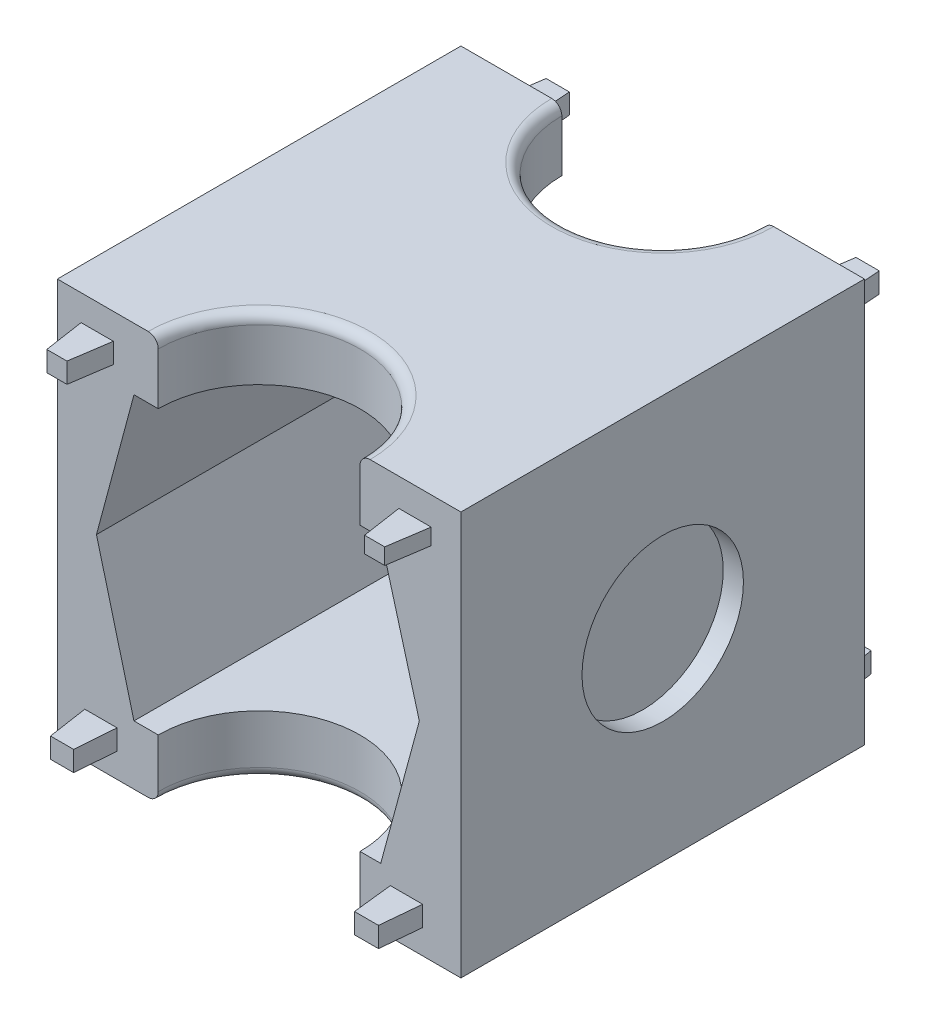
SolidWorks part; units mm, degrees
ref_plane "Front Plane" through (0, 0, 0) normal (0, 0, 1) x (1, 0, 0)
ref_plane "Top Plane" through (0, 0, 0) normal (0, 1, 0) x (1, 0, 0)
ref_plane "Right Plane" through (0, 0, 0) normal (1, 0, 0) x (0, 0, -1)
sketch "Sketch1" plane through (0, 0, 0) normal (1, 0, 0) x (0, 0, -1)
  line L0 (-50, 50) -> (50, 50)
  line L3 (-50, 50) -> (-50, -50)
  line L4 (-50, -50) -> (50, -50)
  line L5 (50, -50) -> (50, 50)
extrude "Boss-Extrude1" add sketch "Sketch1" along normal blind 100
sketch "Sketch2" plane through (0, 0, 0) normal (-1, 0, 0) x (0, 0, 1)
  circle A0 centre (0, 0) radius 20
extrude "Cut-Extrude1" cut sketch "Sketch2" against normal blind 5
sketch "Sketch3" plane through (100, 0, 0) normal (1, 0, 0) x (0, 0, -1)
  circle A0 centre (0, 0) radius 20
extrude "Cut-Extrude2" cut sketch "Sketch3" against normal blind 5
sketch "Sketch4" plane through (0, 0, -50) normal (0, 0, -1) x (-1, 0, 0)
  line L6 (-80.1289, 34.6594) -> (-18.9866, 34.6594)
  line L15 (-80.1289, -35.3406) -> (-18.9866, -35.3406)
  line L17 (-80.1289, 34.6594) -> (-89.6912, 0)
  line L18 (-89.6912, 0) -> (-80.1289, -35.3406)
  line L19 (-18.9866, 34.6594) -> (-9.6912, 0)
  line L20 (-9.6912, 0) -> (-18.9866, -35.3406)
extrude "Cut-Extrude3" cut sketch "Sketch4" against normal through all
sketch "Sketch15" plane through (0, 50, 0) normal (0, 1, 0) x (1, 0, 0)
  line L0 (100, -50) -> (0, -50) construction
  arc A0 (75, -50) -> (25, -50) centre (50, -50) ccw
extrude "Cut-Extrude5" cut sketch "Sketch15" against normal through all and the other way through all
sketch "Sketch16" plane through (0, 50, 0) normal (0, 1, 0) x (1, 0, 0)
  line L0 (100, 50) -> (0, 50) construction
  arc A0 (25, 50) -> (75, 50) centre (50, 50) ccw
extrude "Cut-Extrude6" cut sketch "Sketch16" against normal through all and the other way through all
fillet "Fillet3" radius 2.5 4 edges at (50, -50, -25) (50, -50, 25) (50, 50, -25) (50, 50, 25)
sketch "Sketch17" plane through (0, 0, 50) normal (0, 0, 1) x (1, 0, 0)
  line L2 (84.6212, 43.0797) -> (92.6212, 43.0797)
  line L3 (84.6212, 39.0797) -> (92.6212, 39.0797)
  arc A0 (84.6212, 43.0797) -> (84.6212, 39.0797) centre (84.6212, 41.0797) ccw
  arc A1 (92.6212, 39.0797) -> (92.6212, 43.0797) centre (92.6212, 41.0797) ccw
extrude "Boss-Extrude3" add sketch "Sketch17" along normal blind 10
sketch "Sketch18" plane through (0, 43.0797, 0) normal (0, 1, 0) x (1, 0, 0)
  line L1 (92.6212, -60) -> (84.6212, -60) construction
  line L4 (84.6212, -50) -> (86.1212, -60)
  line L5 (84.6212, -50) -> (82.6212, -50)
  line L6 (82.6212, -50) -> (82.6212, -60)
  line L7 (82.6212, -60) -> (86.1212, -60)
extrude "Cut-Extrude8" cut sketch "Sketch18" against normal blind 10
sketch "Sketch20" plane through (0, 43.0797, 0) normal (0, 1, 0) x (1, 0, 0)
  line L0 (91.1212, -60) -> (94.6212, -60)
  line L1 (92.6212, -60) -> (86.1212, -60) construction
  line L2 (91.1212, -60) -> (92.6212, -50)
  line L3 (94.6212, -60) -> (94.6212, -50)
  line L4 (94.6212, -50) -> (92.6212, -50)
extrude "Cut-Extrude9" cut sketch "Sketch20" against normal blind 10
sketch "Sketch24" plane through (0, 0, 50) normal (0, 0, 1) x (1, 0, 0)
  line L2 (5.8822, 43.5797) -> (13.8822, 43.5797)
  line L3 (5.8822, 38.5797) -> (13.8822, 38.5797)
  arc A0 (5.8822, 43.5797) -> (5.8822, 38.5797) centre (5.8822, 41.0797) ccw
  arc A1 (13.8822, 38.5797) -> (13.8822, 43.5797) centre (13.8822, 41.0797) ccw
extrude "Boss-Extrude4" add sketch "Sketch24" along normal blind 10
sketch "Sketch25" plane through (0, 43.5797, 0) normal (0, 1, 0) x (1, 0, 0)
  line L0 (3.3822, -50) -> (5.8822, -50)
  line L1 (13.8822, -60) -> (5.8822, -60) construction
  line L3 (3.3822, -50) -> (3.3822, -60)
  line L4 (3.3822, -60) -> (7.3822, -60)
  line L5 (5.8822, -50) -> (7.3822, -60)
extrude "Cut-Extrude11" cut sketch "Sketch25" against normal blind 10
sketch "Sketch26" plane through (0, 43.5797, 0) normal (0, 1, 0) x (1, 0, 0)
  line L1 (13.8822, -60) -> (7.3822, -60) construction
  line L2 (12.3822, -60) -> (13.8822, -50)
  line L3 (13.8822, -50) -> (16.3822, -50)
  line L4 (16.3822, -50) -> (16.3822, -60)
  line L5 (16.3822, -60) -> (12.3822, -60)
extrude "Cut-Extrude12" cut sketch "Sketch26" against normal blind 10
sketch "Sketch27" plane through (0, 0, 50) normal (0, 0, 1) x (1, 0, 0)
  line L2 (6.7979, -43.9203) -> (14.7979, -43.9203)
  line L3 (6.7979, -38.9203) -> (14.7979, -38.9203)
  arc A0 (6.7979, -38.9203) -> (6.7979, -43.9203) centre (6.7979, -41.4203) ccw
  arc A1 (14.7979, -43.9203) -> (14.7979, -38.9203) centre (14.7979, -41.4203) ccw
extrude "Boss-Extrude5" add sketch "Sketch27" along normal blind 10
sketch "Sketch29" plane through (0, -43.9203, 0) normal (0, -1, 0) x (1, 0, 0)
  line L1 (6.7979, 60) -> (14.7979, 60) construction
  line L2 (8.2979, 60) -> (6.7979, 50)
  line L3 (6.7979, 50) -> (4.2979, 50)
  line L4 (4.2979, 50) -> (4.2979, 60)
  line L5 (4.2979, 60) -> (8.2979, 60)
extrude "Cut-Extrude13" cut sketch "Sketch29" against normal blind 10
sketch "Sketch30" plane through (0, -43.9203, 0) normal (0, -1, 0) x (1, 0, 0)
  line L0 (14.0479, 60) -> (17.2979, 60)
  line L4 (17.2979, 60) -> (17.2979, 50)
  line L5 (17.2979, 50) -> (14.7979, 50)
  line L6 (8.2979, 60) -> (14.7979, 60) construction
  line L7 (14.0479, 60) -> (14.7979, 50)
extrude "Cut-Extrude15" cut sketch "Sketch30" against normal blind 10
sketch "Sketch31" plane through (0, 0, 50) normal (0, 0, 1) x (1, 0, 0)
  line L2 (82.5173, -38.9203) -> (90.5173, -38.9203)
  line L3 (82.5173, -43.9203) -> (90.5173, -43.9203)
  arc A0 (82.5173, -38.9203) -> (82.5173, -43.9203) centre (82.5173, -41.4203) ccw
  arc A1 (90.5173, -43.9203) -> (90.5173, -38.9203) centre (90.5173, -41.4203) ccw
extrude "Boss-Extrude6" add sketch "Sketch31" along normal blind 10
sketch "Sketch33" plane through (0, -43.9203, 0) normal (0, -1, 0) x (1, 0, 0)
  line L1 (82.5173, 60) -> (90.5173, 60) construction
  line L2 (83.6212, 60) -> (82.5173, 50)
  line L3 (82.5173, 50) -> (80.0173, 50)
  line L4 (80.0173, 50) -> (80.0173, 60)
  line L5 (80.0173, 60) -> (83.6212, 60)
extrude "Cut-Extrude16" cut sketch "Sketch33" against normal blind 10
sketch "Sketch34" plane through (0, -43.9203, 0) normal (0, -1, 0) x (1, 0, 0)
  line L1 (83.6212, 60) -> (90.5173, 60) construction
  line L2 (89.5693, 60) -> (90.5173, 50)
  line L3 (90.5173, 50) -> (93.0173, 50)
  line L4 (93.0173, 50) -> (93.0173, 60)
  line L5 (93.0173, 60) -> (90.5173, 60) construction
  line L6 (93.0173, 50) -> (93.0173, 60) construction
  line L7 (93.0173, 60) -> (89.5693, 60)
extrude "Cut-Extrude17" cut sketch "Sketch34" against normal blind 10
sketch "Sketch35" plane through (0, 0, -50) normal (0, 0, -1) x (-1, 0, 0)
  line L2 (-17.6085, 43.5797) -> (-9.6085, 43.5797)
  line L3 (-17.6085, 38.5797) -> (-9.6085, 38.5797)
  arc A0 (-17.6085, 43.5797) -> (-17.6085, 38.5797) centre (-17.6085, 41.0797) ccw
  arc A1 (-9.6085, 38.5797) -> (-9.6085, 43.5797) centre (-9.6085, 41.0797) ccw
extrude "Boss-Extrude7" add sketch "Sketch35" along normal blind 10
sketch "Sketch36" plane through (0, 43.5797, 0) normal (0, 1, 0) x (1, 0, 0)
  line L1 (9.6085, 60) -> (17.6085, 60) construction
  line L2 (11.1085, 60) -> (9.6085, 50)
  line L3 (9.6085, 50) -> (7.1085, 50)
  line L4 (7.1085, 50) -> (7.1085, 60)
  line L5 (7.1085, 60) -> (11.1085, 60)
extrude "Cut-Extrude18" cut sketch "Sketch36" against normal blind 10
sketch "Sketch37" plane through (0, 43.5797, 0) normal (0, 1, 0) x (1, 0, 0)
  line L1 (11.1085, 60) -> (17.6085, 60) construction
  line L2 (16.8585, 60) -> (17.6085, 50)
  line L3 (17.6085, 50) -> (20.1085, 50)
  line L4 (20.1085, 50) -> (20.1085, 60)
  line L5 (20.1085, 60) -> (16.8585, 60)
extrude "Cut-Extrude19" cut sketch "Sketch37" against normal blind 10
sketch "Sketch38" plane through (0, 0, -50) normal (0, 0, -1) x (-1, 0, 0)
  line L2 (-17.3305, -38.9203) -> (-9.3305, -38.9203)
  line L3 (-17.3305, -43.9203) -> (-9.3305, -43.9203)
  arc A0 (-17.3305, -38.9203) -> (-17.3305, -43.9203) centre (-17.3305, -41.4203) ccw
  arc A1 (-9.3305, -43.9203) -> (-9.3305, -38.9203) centre (-9.3305, -41.4203) ccw
extrude "Boss-Extrude8" add sketch "Sketch38" along normal blind 10
sketch "Sketch40" plane through (0, -43.9203, 0) normal (0, -1, 0) x (1, 0, 0)
  line L1 (17.3305, -60) -> (9.3305, -60) construction
  line L2 (10.8305, -60) -> (9.3305, -50)
  line L3 (9.3305, -50) -> (6.8305, -50)
  line L4 (6.8305, -50) -> (6.8305, -60)
  line L5 (6.8305, -60) -> (10.8305, -60)
extrude "Cut-Extrude20" cut sketch "Sketch40" against normal blind 10
sketch "Sketch41" plane through (0, -43.9203, 0) normal (0, -1, 0) x (1, 0, 0)
  line L2 (16.5805, -60) -> (17.3305, -50)
  line L3 (17.3305, -50) -> (19.8305, -50)
  line L4 (19.8305, -50) -> (19.8305, -60)
  line L5 (19.8305, -60) -> (16.5805, -60)
extrude "Cut-Extrude21" cut sketch "Sketch41" against normal blind 10
sketch "Sketch42" plane through (0, 0, -50) normal (0, 0, -1) x (-1, 0, 0)
  line L2 (-94.397, 43.5797) -> (-86.397, 43.5797)
  line L3 (-94.397, 38.5797) -> (-86.397, 38.5797)
  arc A0 (-94.397, 43.5797) -> (-94.397, 38.5797) centre (-94.397, 41.0797) ccw
  arc A1 (-86.397, 38.5797) -> (-86.397, 43.5797) centre (-86.397, 41.0797) ccw
extrude "Boss-Extrude9" add sketch "Sketch42" along normal blind 10
sketch "Sketch43" plane through (0, 43.5797, 0) normal (0, 1, 0) x (1, 0, 0)
  line L1 (86.397, 60) -> (94.397, 60) construction
  line L2 (87.897, 60) -> (86.397, 50)
  line L3 (86.397, 50) -> (83.897, 50)
  line L4 (83.897, 50) -> (83.897, 60)
  line L5 (83.897, 60) -> (87.897, 60)
extrude "Cut-Extrude22" cut sketch "Sketch43" against normal blind 10
sketch "Sketch44" plane through (0, 43.5797, 0) normal (0, 1, 0) x (1, 0, 0)
  line L1 (87.897, 60) -> (94.397, 60) construction
  line L2 (93.647, 60) -> (94.397, 50)
  line L3 (94.397, 50) -> (96.897, 50)
  line L4 (96.897, 50) -> (96.897, 60)
  line L5 (96.897, 60) -> (93.647, 60)
extrude "Cut-Extrude23" cut sketch "Sketch44" against normal blind 10
sketch "Sketch45" plane through (0, 0, -50) normal (0, 0, -1) x (-1, 0, 0)
  line L2 (-93.1405, -38.9203) -> (-85.1405, -38.9203)
  line L3 (-93.1405, -43.9203) -> (-85.1405, -43.9203)
  arc A0 (-93.1405, -38.9203) -> (-93.1405, -43.9203) centre (-93.1405, -41.4203) ccw
  arc A1 (-85.1405, -43.9203) -> (-85.1405, -38.9203) centre (-85.1405, -41.4203) ccw
extrude "Boss-Extrude10" add sketch "Sketch45" along normal blind 10
sketch "Sketch47" plane through (0, -43.9203, 0) normal (0, -1, 0) x (1, 0, 0)
  line L1 (93.1405, -60) -> (85.1405, -60) construction
  line L2 (86.6405, -60) -> (85.1405, -50)
  line L3 (85.1405, -50) -> (82.6405, -50)
  line L4 (82.6405, -50) -> (82.6405, -60)
  line L5 (82.6405, -60) -> (86.6405, -60)
extrude "Cut-Extrude24" cut sketch "Sketch47" against normal blind 10
sketch "Sketch48" plane through (0, -43.9203, 0) normal (0, -1, 0) x (1, 0, 0)
  line L1 (93.1405, -60) -> (86.6405, -60) construction
  line L2 (91.6479, -60) -> (93.1405, -50)
  line L3 (93.1405, -50) -> (95.6405, -50)
  line L4 (95.6405, -50) -> (95.6405, -60)
  line L5 (95.6405, -60) -> (91.6479, -60)
extrude "Cut-Extrude25" cut sketch "Sketch48" against normal blind 10
